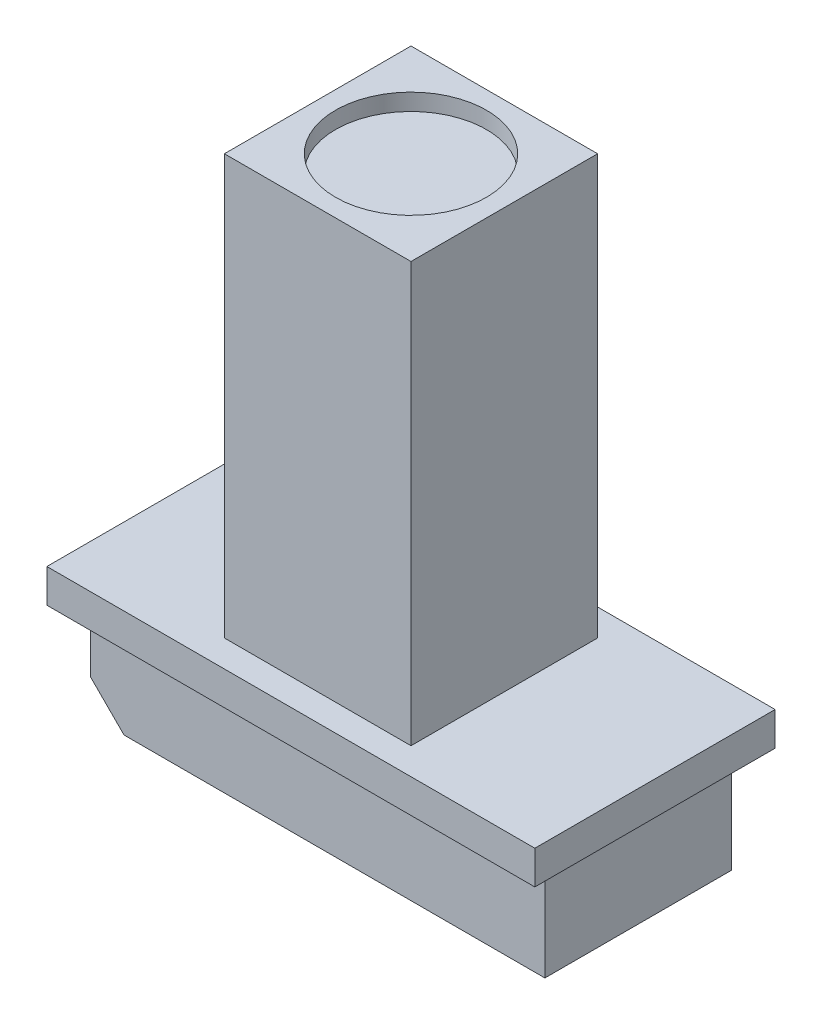
SolidWorks part; units mm, degrees
ref_plane "Front" through (0, 0, 0) normal (0, 0, 1) x (1, 0, 0)
ref_plane "Top" through (0, 0, 0) normal (0, 1, 0) x (1, 0, 0)
ref_plane "Right" through (0, 0, 0) normal (1, 0, 0) x (0, 0, -1)
sketch "Эскиз1" plane through (0, 0, 0) normal (0, 1, 0) x (1, 0, 0)
  line L5 (2.781, -2.781) -> (-2.781, -2.781)
  line L6 (2.781, -2.781) -> (2.781, 2.781)
  line L7 (2.781, 2.781) -> (-2.781, 2.781)
  line L8 (-2.781, -2.781) -> (-2.781, 2.781)
  line L9 (2.781, -2.781) -> (-2.781, 2.781) construction
  line L10 (2.781, 2.781) -> (-2.781, -2.781) construction
  line L16 (6.772, -2.781) -> (-6.772, -2.781) construction
  line L17 (6.772, -2.781) -> (6.772, 2.781) construction
  line L18 (6.772, 2.781) -> (-6.772, 2.781) construction
  line L19 (-6.772, -2.781) -> (-6.772, 2.781) construction
  line L20 (6.772, -2.781) -> (-6.772, 2.781) construction
  line L21 (6.772, 2.781) -> (-6.772, -2.781) construction
  point P0 (0, 0)
  point P18 (0, 0)
  dimension "D3" = 5.562
  dimension "D6" = 13.544
extrude "Бобышка-Вытянуть2" add sketch "Эскиз1" along normal blind 12.5
sketch "Эскиз5" plane through (0, 12.5, 0) normal (0, 1, 0) x (1, 0, 0)
  line L0 (-2.781, 2.781) -> (2.781, -2.781) construction
  line L1 (2.781, 2.781) -> (-2.781, -2.781) construction
  circle A0 centre (0, 0) radius 2.25
  dimension "D1" = 4.5
extrude "Вырез-Вытянуть2" cut sketch "Эскиз5" against normal blind 0.5
sketch "Эскиз6" plane through (0, 0, 0) normal (0, -1, 0) x (1, 0, 0)
  line L4 (2.781, -2.781) -> (-2.781, -2.781) construction
  line L5 (2.781, -2.781) -> (2.781, 2.781) construction
  line L6 (2.781, 2.781) -> (-2.781, 2.781) construction
  line L7 (-2.781, -2.781) -> (-2.781, 2.781) construction
  line L8 (2.781, -2.781) -> (-2.781, 2.781) construction
  line L9 (2.781, 2.781) -> (-2.781, -2.781) construction
  line L10 (6.772, -2.781) -> (-6.772, -2.781) construction
  line L11 (6.772, -2.781) -> (6.772, 2.781) construction
  line L12 (6.772, 2.781) -> (-6.772, 2.781) construction
  line L17 (-6.772, -2.781) -> (-6.772, 2.781) construction
  line L18 (6.772, -2.781) -> (-6.772, 2.781) construction
  line L19 (6.772, 2.781) -> (-6.772, -2.781) construction
  line L21 (7.272, -3.581) -> (-7.272, -3.581)
  line L22 (7.272, -3.581) -> (7.272, 3.581)
  line L23 (7.272, 3.581) -> (-7.272, 3.581)
  line L24 (-7.272, -3.581) -> (-7.272, 3.581)
  line L25 (7.272, -3.581) -> (-7.272, 3.581) construction
  line L26 (7.272, 3.581) -> (-7.272, -3.581) construction
  point P0 (0, 0)
  point P5 (0, 0)
  point P11 (0, 0)
  dimension "D1" = 13.544
  dimension "D2" = 5.562
  dimension "D3" = 0.5
  dimension "D4" = 0.8
extrude "Бобышка-Вытянуть3" add sketch "Эскиз6" along normal blind 1 separate body
sketch "Эскиз7" plane through (0, -1, 0) normal (0, -1, 0) x (1, 0, 0)
  line L0 (2.781, -2.781) -> (-2.781, -2.781) construction
  line L1 (2.781, -2.781) -> (2.781, 2.781) construction
  line L2 (2.781, 2.781) -> (-2.781, 2.781) construction
  line L3 (-2.781, -2.781) -> (-2.781, 2.781) construction
  line L4 (2.781, -2.781) -> (-2.781, 2.781) construction
  line L5 (2.781, 2.781) -> (-2.781, -2.781) construction
  line L6 (6.772, -2.781) -> (-6.772, -2.781)
  line L7 (6.772, -2.781) -> (6.772, 2.781)
  line L8 (6.772, 2.781) -> (-6.772, 2.781)
  line L9 (-6.772, -2.781) -> (-6.772, 2.781)
  line L10 (6.772, -2.781) -> (-6.772, 2.781) construction
  line L11 (6.772, 2.781) -> (-6.772, -2.781) construction
  point P0 (0, 0)
  point P5 (0, 0)
  dimension "D1" = 5.562
  dimension "D2" = 13.544
extrude "Бобышка-Вытянуть4" add sketch "Эскиз7" along normal blind 3
chamfer "Фаска2" distance 1 angle 45 1 edges at (-6.772, -4, 0)
